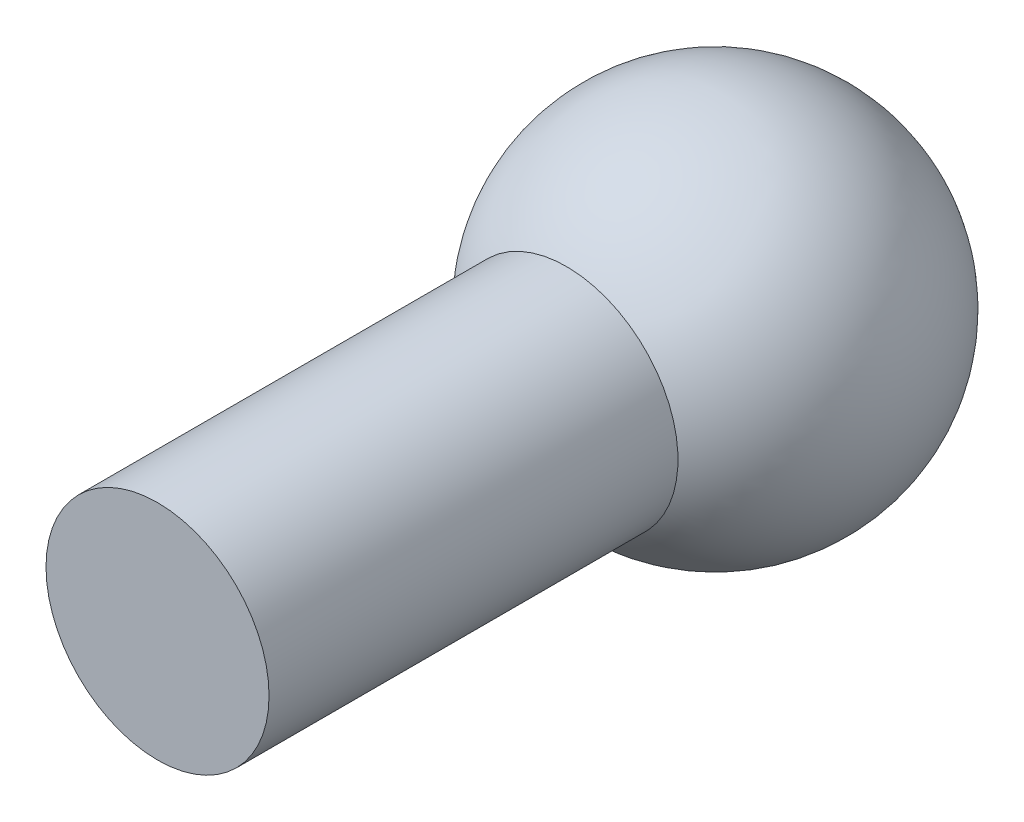
SolidWorks part; units mm, degrees
ref_plane "前视基准面" through (0, 0, 0) normal (0, 0, 1) x (1, 0, 0)
ref_plane "上视基准面" through (0, 0, 0) normal (0, 1, 0) x (1, 0, 0)
ref_plane "右视基准面" through (0, 0, 0) normal (1, 0, 0) x (0, 0, -1)
sketch "草图1" plane through (0, 0, 0) normal (0, 0, 1) x (1, 0, 0)
  line L0 (0, -1000) -> (0, 49000) construction
  line L1 (0, -5) -> (0, 5)
  arc A0 (0, 5) -> (0, -5) centre (0, 0) ccw
  dimension "D1" = 10
revolve "旋转1" add sketch "草图1" angle 360 about L0
sketch "草图2" plane through (0, 0, 0) normal (0, 0, 1) x (1, 0, 0)
  circle A0 centre (0, 0) radius 3
  dimension "D1" = 6
extrude "拉伸1" add sketch "草图2" along normal blind 15
